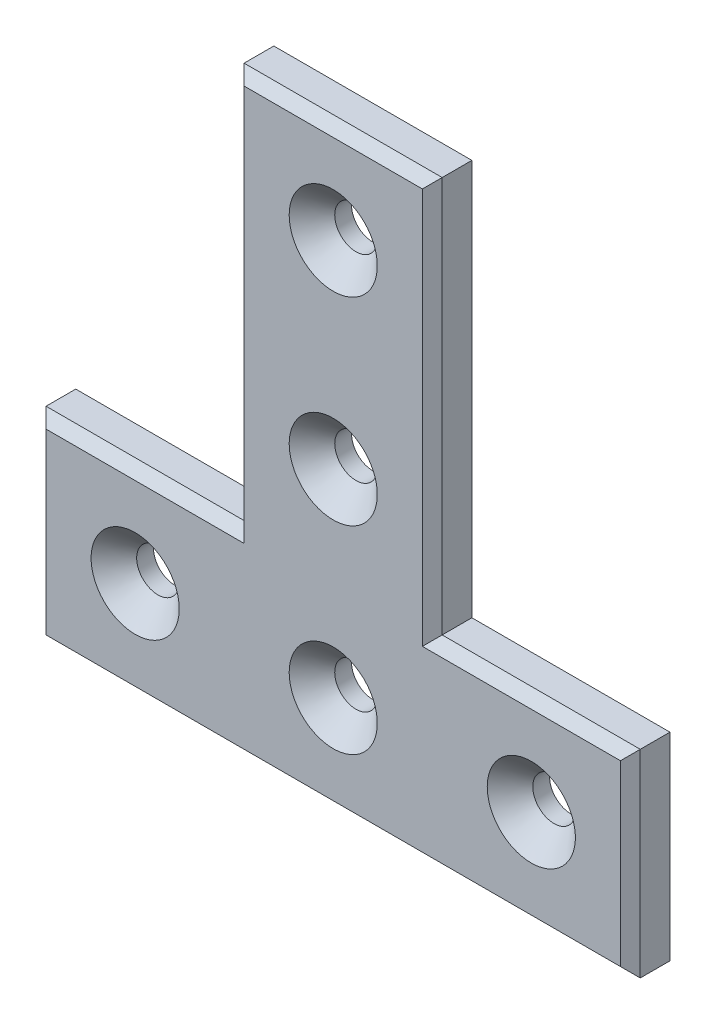
SolidWorks part; units mm, degrees
ref_plane "Front Plane" through (0, 0, 0) normal (0, 0, 1) x (1, 0, 0)
ref_plane "Top Plane" through (0, 0, 0) normal (0, 1, 0) x (1, 0, 0)
ref_plane "Right Plane" through (0, 0, 0) normal (1, 0, 0) x (0, 0, -1)
sketch "Sketch1" plane through (0, 0, 0) normal (0, 0, 1) x (1, 0, 0)
  line L0 (10, 10) -> (30, 10)
  line L1 (-30, -10) -> (30, -10)
  line L2 (-30, -10) -> (-30, 10)
  line L3 (-30, 10) -> (-10, 10)
  line L4 (30, -10) -> (30, 10)
  line L5 (-30, -10) -> (30, 10) construction
  line L6 (-30, 10) -> (30, -10) construction
  line L8 (-10, 10) -> (-10, 50)
  line L9 (-10, 50) -> (10, 50)
  line L10 (10, 10) -> (10, 50)
  line L11 (10, 10) -> (-10, 10) construction
  line L12 (-20, 0) -> (20, 0) construction
  line L13 (0, 50) -> (0, 0) construction
  circle A0 centre (0, 20) radius 2.15
  circle A1 centre (20, 0) radius 2.15
  circle A2 centre (-20, 0) radius 2.15
  circle A3 centre (0, 40) radius 2.15
  circle A4 centre (0, 0) radius 2.15
  point P0 (0, 0)
  point P10 (0, 50)
  point P16 (0, 0)
  dimension "D3" = 4.3
  dimension "D1" = 20
  dimension "D2" = 20
  dimension "D4" = 20
  dimension "D5" = 20
  dimension "D6" = 20
  dimension "D7" = 10
  dimension "D8" = 10
extrude "Boss-Extrude1" add sketch "Sketch1" along normal blind 4
sketch "Sketch2" plane through (0, 0, 0) normal (0, 0, -1) x (-1, 0, 0)
  line L0 (-20, 0) -> (20, 0) construction
  line L1 (0, 40) -> (0, 20) construction
  line L2 (-26, -2.85) -> (26, -2.85)
  line L4 (-26, -2.85) -> (-26, 2.85)
  line L5 (-26, 2.85) -> (26, 2.85)
  line L6 (26, -2.85) -> (26, 2.85)
  line L7 (-26, -2.85) -> (26, 2.85) construction
  line L8 (-26, 2.85) -> (26, -2.85) construction
  line L13 (-2.85, 14) -> (2.85, 14)
  line L14 (-2.85, 14) -> (-2.85, 46)
  line L15 (-2.85, 46) -> (2.85, 46)
  line L16 (2.85, 14) -> (2.85, 46)
  line L17 (-2.85, 14) -> (2.85, 46) construction
  line L18 (-2.85, 46) -> (2.85, 14) construction
  point P12 (0, 20)
  point P13 (0, 30)
  point P19 (0, 0)
  dimension "D1" = 5.7
  dimension "D2" = 6
  dimension "D3" = 6
chamfer "Chamfer2" distance 2.3 angle 45 5 edges at (22.15, 0, 4) (2.15, 0, 4) (-17.85, 0, 4) (2.15, 20, 4) (2.15, 40, 4)
chamfer "Chamfer3" distance 1 angle 45 8 edges at (0, -10, 4) (-30, 0, 4) (-20, 10, 4) (-10, 30, 4) (0, 50, 4) (10, 30, 4) (20, 10, 4) (30, 0, 4)
